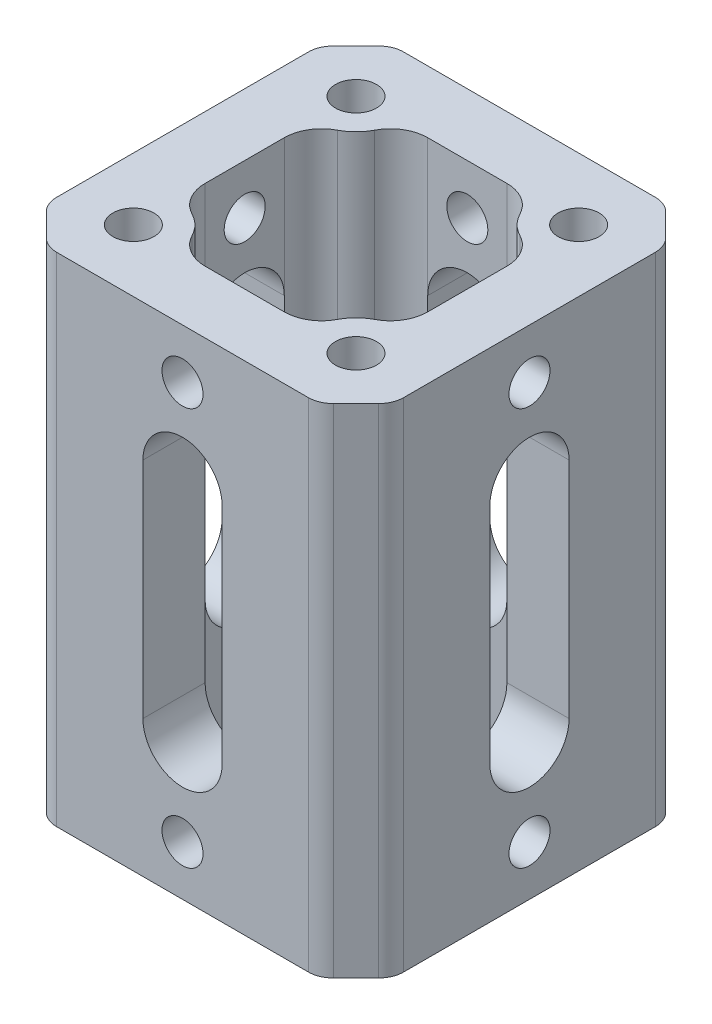
SolidWorks part; units mm, degrees
material "6061 合金"
ref_plane "前视基准面" through (0, 0, 0) normal (0, 0, 1) x (1, 0, 0)
ref_plane "上视基准面" through (0, 0, 0) normal (0, 1, 0) x (1, 0, 0)
ref_plane "右视基准面" through (0, 0, 0) normal (1, 0, 0) x (0, 0, -1)
sketch "草图1" plane through (0, 0, 0) normal (0, 1, 0) x (1, 0, 0)
  line L1 (-13.95, -13.95) -> (13.95, -13.95)
  line L2 (-13.95, -13.95) -> (-13.95, 13.95)
  line L3 (-13.95, 13.95) -> (13.95, 13.95)
  line L4 (13.95, -13.95) -> (13.95, 13.95)
  line L5 (0, 13.95) -> (0, -13.95) construction
  line L6 (-13.95, 0) -> (13.95, 0) construction
  point P0 (0, 0)
  dimension "D1" = 27.9
extrude "凸台-拉伸1" add sketch "草图1" along normal mid plane 40
sketch "草图5" plane through (0, -20, 0) normal (0, -1, 0) x (1, 0, 0)
  line L0 (13.95, 13.95) -> (13.95, -13.95) construction
  line L1 (-8.95, -8.95) -> (8.95, -8.95) construction
  line L2 (-8.95, -8.95) -> (-8.95, 8.95) construction
  line L3 (-8.95, 8.95) -> (8.95, 8.95) construction
  line L4 (8.95, -8.95) -> (8.95, 8.95) construction
  line L5 (0, 8.95) -> (0, -8.95) construction
  line L6 (-8.95, 0) -> (8.95, 0) construction
  line L7 (-13.95, 13.95) -> (13.95, 13.95) construction
  point P0 (0, 0)
  dimension "D1" = 5
  dimension "D2" = 5
hole_wizard "M4 螺纹孔2" positions "草图6" profile "草图7" tap size "M4" standard "GB" end condition through all
sketch "草图6" plane through (0, -20, 0) normal (0, -1, 0) x (-1, 0, 0)
  point P0 (8.95, -8.95)
  point P3 (8.95, 8.95)
  point P6 (-8.95, 8.95)
  point P9 (-8.95, -8.95)
sketch "草图7" plane through (-8.95, -20, 8.95) normal (1, 0, 0) x (0, 0, -1)
  line L0 (0, 0) -> (0, 40)
  line L1 (0, 40) -> (1.65, 40)
  line L2 (1.65, 40) -> (1.65, 0)
  line L5 (1.65, 0) -> (0, 0)
  line L11 (0, -6.35) -> (0, 107.95) construction
  dimension "通孔螺纹孔钻头直径" = 3.3
  dimension "通孔螺纹孔钻头深度" = 40
cosmetic thread "孔螺蚊线5" parameters "D2"=4
cosmetic thread "孔螺蚊线6" parameters "D2"=4
cosmetic thread "孔螺蚊线7" parameters "D2"=4
cosmetic thread "孔螺蚊线8" parameters "D2"=4
sketch "草图8" plane through (0, -20, 0) normal (0, -1, 0) x (1, 0, 0)
  line L0 (-13.95, 13.95) -> (13.95, 13.95) construction
  line L1 (-8.95, -8.95) -> (8.95, -8.95)
  line L2 (-8.95, -8.95) -> (-8.95, 8.95)
  line L3 (-8.95, 8.95) -> (8.95, 8.95)
  line L4 (8.95, -8.95) -> (8.95, 8.95)
  line L5 (0, 8.95) -> (0, -8.95) construction
  line L6 (-8.95, 0) -> (8.95, 0) construction
  line L7 (13.95, 13.95) -> (13.95, -13.95) construction
  circle A0 centre (8.95, 8.95) radius 3.5
  circle A1 centre (8.95, -8.95) radius 3.5
  circle A2 centre (-8.95, -8.95) radius 3.5
  circle A3 centre (-8.95, 8.95) radius 3.5
  point P8 (0, 0)
  dimension "D1" = 7
  dimension "D2" = 5
  dimension "D3" = 5
extrude "切除-拉伸1" cut sketch "草图8" against normal mid plane 92 contours A3 L2 A2 L1 A1 L4 A0 L3
chamfer "倒角1" distance 3 angle 45 4 edges at (13.95, 0, 13.95) (13.95, 0, -13.95) (-13.95, 0, -13.95) (-13.95, 0, 13.95)
sketch "草图9" plane through (-13.95, 0, 0) normal (-1, 0, 0) x (0, 0, 1)
  line L0 (0, -16) -> (0, 16) construction
  point P4 (0, 0)
  dimension "D1" = 32
hole_wizard "M4 螺纹孔3" positions "草图10" profile "草图11" tap size "M4" standard "GB" end condition through all
sketch "草图10" plane through (-13.95, 0, 0) normal (-1, 0, 0) x (0, 0, 1)
  point P0 (0, 16)
  point P3 (0, -16)
sketch "草图11" plane through (-13.95, 16, 0) normal (0, 1, 0) x (0, 0, 1)
  line L0 (0, 0) -> (0, 27.9)
  line L1 (0, 27.9) -> (1.65, 27.9)
  line L2 (1.65, 27.9) -> (1.65, 0)
  line L5 (1.65, 0) -> (0, 0)
  line L11 (0, -6.35) -> (0, 107.95) construction
  dimension "通孔螺纹孔钻头直径" = 3.3
  dimension "通孔螺纹孔钻头深度" = 27.9
cosmetic thread "孔螺蚊线9" parameters "D2"=4
cosmetic thread "孔螺蚊线10" parameters "D2"=4
cosmetic thread "装饰螺纹线1" parameters "D2"=4
cosmetic thread "装饰螺纹线2" parameters "D2"=4
sketch "草图12" plane through (0, 0, 13.95) normal (0, 0, 1) x (1, 0, 0)
  line L0 (0, -16) -> (0, 16) construction
  point P4 (0, 0)
  dimension "D1" = 32
hole_wizard "M4 螺纹孔4" positions "草图13" profile "草图14" tap size "M4" standard "GB" end condition through all
sketch "草图13" plane through (0, 0, 13.95) normal (0, 0, 1) x (1, 0, 0)
  point P0 (0, 16)
  point P3 (0, -16)
sketch "草图14" plane through (0, 16, 13.95) normal (1, 0, 0) x (0, -1, 0)
  line L0 (0, 0) -> (0, 27.9)
  line L1 (0, 27.9) -> (1.65, 27.9)
  line L2 (1.65, 27.9) -> (1.65, 0)
  line L5 (1.65, 0) -> (0, 0)
  line L11 (0, -6.35) -> (0, 107.95) construction
  dimension "通孔螺纹孔钻头直径" = 3.3
  dimension "通孔螺纹孔钻头深度" = 27.9
cosmetic thread "孔螺蚊线11" parameters "D2"=4
cosmetic thread "孔螺蚊线12" parameters "D2"=4
cosmetic thread "装饰螺纹线3" parameters "D2"=4
cosmetic thread "装饰螺纹线4" parameters "D2"=4
fillet "圆角1" radius 2 8 edges at (13.95, 0, -10.95) (10.95, 0, -13.95) (-10.95, 0, -13.95) (-13.95, 0, -10.95) (10.95, 0, 13.95) (13.95, 0, 10.95) (-13.95, 0, 10.95) (-10.95, 0, 13.95)
fillet "圆角2" radius 3 8 edges at (-5.45, 0, 8.95) (5.45, 0, 8.95) (5.45, 0, -8.95) (-5.45, 0, -8.95) (-8.95, 0, -5.45) (-8.95, 0, 5.45) (8.95, 0, 5.45) (8.95, 0, -5.45)
sketch "草图15" plane through (-13.95, 0, 0) normal (-1, 0, 0) x (0, 0, 1)
  line L0 (0, -9) -> (0, 9) construction
  line L1 (-3.1837, -9) -> (-3.1837, 9)
  line L2 (3.1837, -9) -> (3.1837, 9)
  line L3 (3.1837, -20) -> (3.1837, 20) construction
  arc A0 (-3.1837, -9) -> (3.1837, -9) centre (0, -9) ccw
  arc A1 (3.1837, 9) -> (-3.1837, 9) centre (0, 9) ccw
  point P2 (0, 0)
  dimension "D1" = 18
extrude "切除-拉伸2" cut sketch "草图15" against normal mid plane 92
sketch "草图16" plane through (0, 0, -13.95) normal (0, 0, -1) x (-1, 0, 0)
  line L0 (0, -9) -> (0, 9) construction
  line L1 (-3.1837, -9) -> (-3.1837, 9)
  line L2 (3.1837, -9) -> (3.1837, 9)
  line L3 (3.1837, -20) -> (3.1837, 20) construction
  arc A0 (-3.1837, -9) -> (3.1837, -9) centre (0, -9) ccw
  arc A1 (3.1837, 9) -> (-3.1837, 9) centre (0, 9) ccw
  point P2 (0, 0)
  dimension "D1" = 18
extrude "切除-拉伸3" cut sketch "草图16" against normal mid plane 92
equation "\"D2@草图5\"=\"D1@草图5\""
